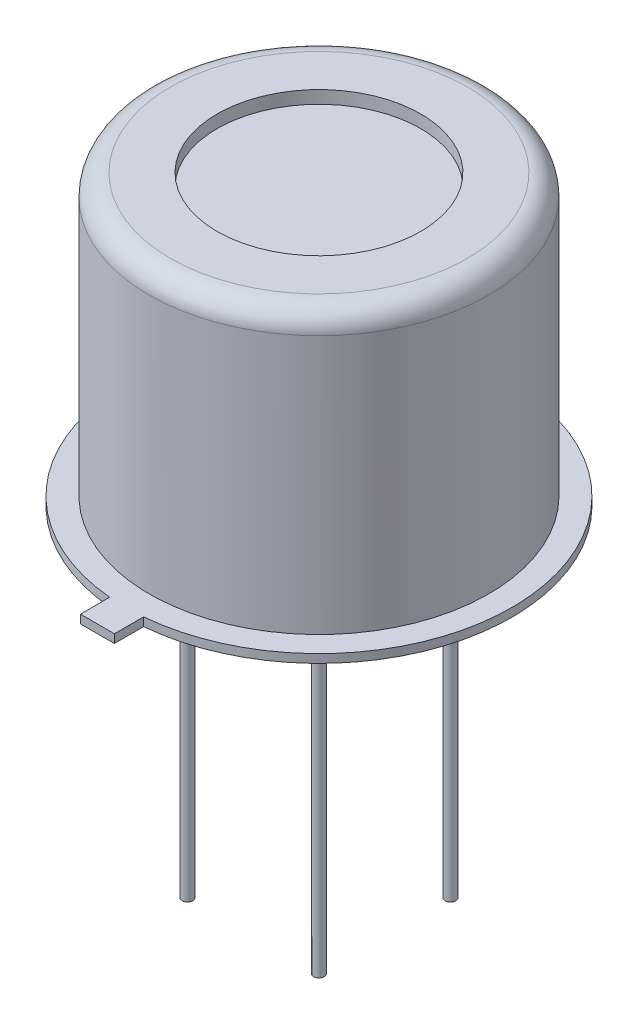
SolidWorks part; units mm, degrees
ref_plane "前视基准面" through (0, 0, 0) normal (0, 0, 1) x (1, 0, 0)
ref_plane "上视基准面" through (0, 0, 0) normal (0, 1, 0) x (1, 0, 0)
ref_plane "右视基准面" through (0, 0, 0) normal (1, 0, 0) x (0, 0, -1)
sketch "草图1" plane through (0, 0, 0) normal (0, 1, 0) x (1, 0, 0)
  circle A0 centre (0, 0) radius 4
  dimension "D1" = 8
extrude "凸台-拉伸1" add sketch "草图1" along normal blind 6.6
sketch "草图2" plane through (0, 0, 0) normal (0, -1, 0) x (1, 0, 0)
  circle A1 centre (0, 0) radius 4.55
  dimension "D1" = 9.1
extrude "凸台-拉伸2" add sketch "草图2" along normal blind 0.2
sketch "草图5" plane through (0, -0.2, 0) normal (0, -1, 0) x (1, 0, 0)
  line L0 (0, 6.2322) -> (0, -6.1683) construction
  line L2 (-0.4, 5.2223) -> (0.4, 5.2223)
  line L3 (-0.4, 5.2223) -> (-0.4, 4.2294)
  line L4 (-0.4, 4.2294) -> (0.4, 4.2294)
  line L5 (0.4, 5.2223) -> (0.4, 4.2294)
  dimension "D1" = 0.8
extrude "凸台-拉伸4" add sketch "草图5" against normal blind 0.2
sketch "草图4" plane through (0, 6.6, 0) normal (0, 1, 0) x (1, 0, 0)
  circle A0 centre (0, 0) radius 2.4
  dimension "D1" = 4.8
extrude "切除-拉伸1" cut sketch "草图4" against normal blind 0.3
fillet "圆角1" radius 0.5 1 edges at (0, 6.6, 4)
sketch "草图3" plane through (0, -0.2, 0) normal (0, -1, 0) x (1, 0, 0)
  line L0 (-6.798, 0) -> (8.1158, 0) construction
  line L1 (0, 7.3038) -> (0, -6.8386) construction
  circle A0 centre (-1.55, 1.55) radius 0.125
  circle A1 centre (1.55, 1.55) radius 0.125
  circle A2 centre (1.55, -1.55) radius 0.125
  circle A3 centre (-1.55, -1.55) radius 0.125
  dimension "D1" = 0.25
  dimension "D2" = 3.1
  dimension "D3" = 3.1
extrude "凸台-拉伸3" add sketch "草图3" along normal blind 8
